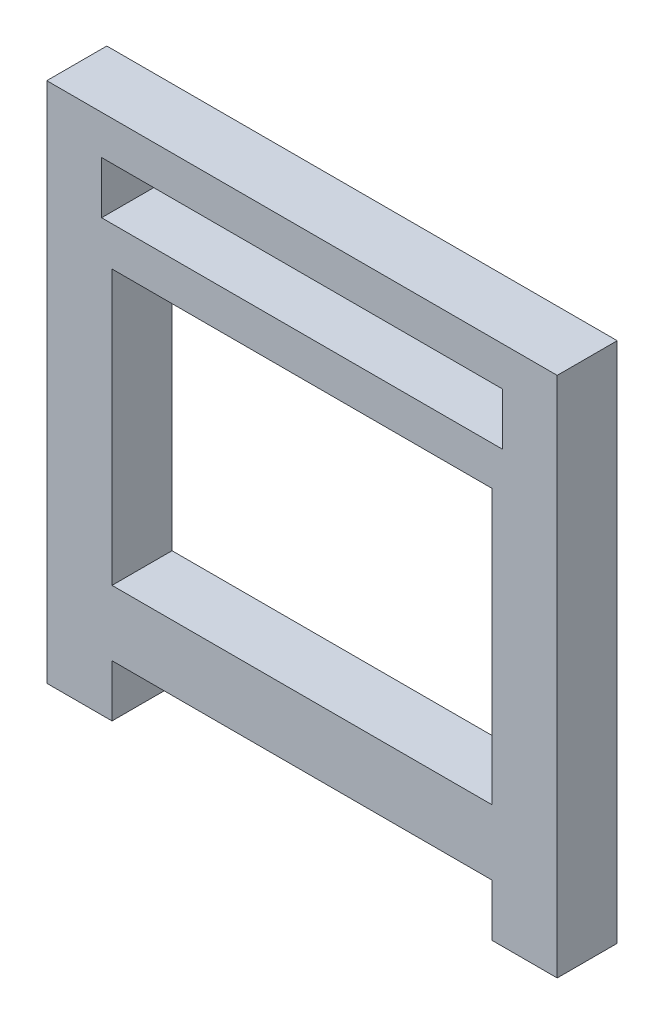
SolidWorks part; units mm, degrees
ref_plane "Front Plane" through (0, 0, 0) normal (0, 0, 1) x (1, 0, 0)
ref_plane "Top Plane" through (0, 0, 0) normal (0, 1, 0) x (1, 0, 0)
ref_plane "Right Plane" through (0, 0, 0) normal (1, 0, 0) x (0, 0, -1)
sketch "Sketch1" plane through (0, 0, 0) normal (0, 0, 1) x (1, 0, 0)
  line L0 (0, 0) -> (0, -2)
  line L1 (2.5, 0) -> (17.06, 0)
  line L2 (0, 0) -> (0, 18)
  line L3 (0, 18) -> (19.56, 18)
  line L4 (19.56, 0) -> (19.56, 18)
  line L5 (0, -2) -> (2.5, -2)
  line L6 (2.5, -2) -> (2.5, 0)
  line L7 (19.56, 0) -> (19.56, -2)
  line L8 (19.56, -2) -> (17.06, -2)
  line L9 (17.06, -2) -> (17.06, 0)
  line L12 (2.5, 2.5) -> (17.06, 2.5)
  line L13 (2.5, 2.5) -> (2.5, 13)
  line L14 (2.5, 13) -> (17.06, 13)
  line L15 (17.06, 2.5) -> (17.06, 13)
  line L16 (2.1, 14.5) -> (17.46, 14.5)
  line L17 (2.1, 14.5) -> (2.1, 16.5)
  line L18 (2.1, 16.5) -> (17.46, 16.5)
  line L19 (17.46, 14.5) -> (17.46, 16.5)
  dimension "D1" = 18
  dimension "D2" = 2.5
  dimension "D3" = 14.56
  dimension "D4" = 2
  dimension "D5" = 2
  dimension "D6" = 2.5
  dimension "D7" = 2.5
  dimension "D8" = 10.5
  dimension "D9" = 2
  dimension "D10" = 1.5
  dimension "D12" = 0.4
extrude "Boss-Extrude1" add sketch "Sketch1" along normal blind 2.3
